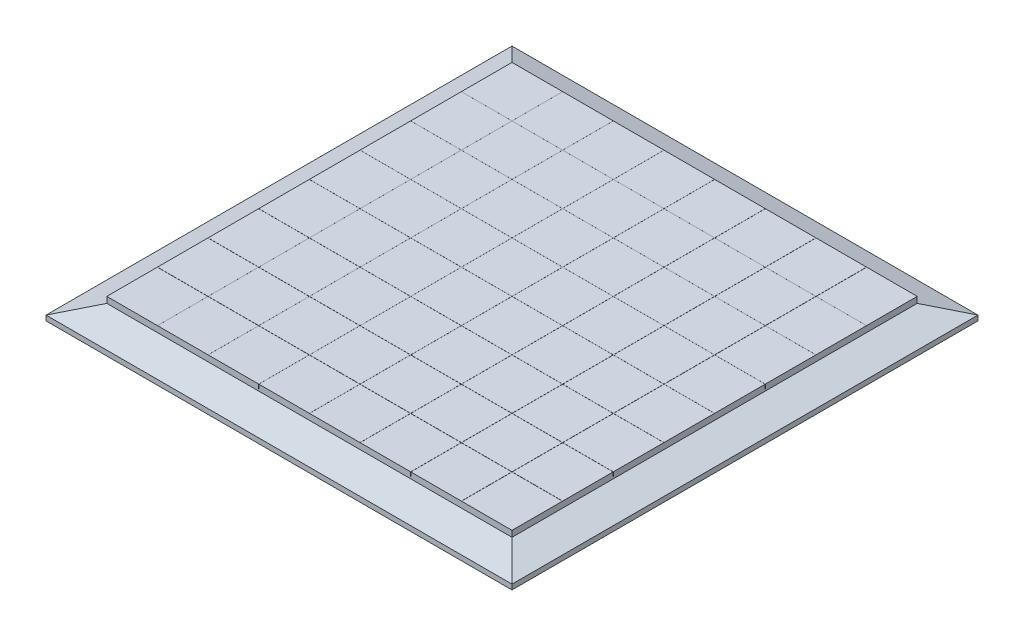
SolidWorks part; units mm, degrees
ref_plane "Ön Düzlem" through (0, 0, 0) normal (0, 0, 1) x (1, 0, 0)
ref_plane "Üst Düzlem" through (0, 0, 0) normal (0, 1, 0) x (1, 0, 0)
ref_plane "Sağ Düzlem" through (0, 0, 0) normal (1, 0, 0) x (0, 0, -1)
sketch "Çizim1" plane through (0, 0, 0) normal (0, 1, 0) x (1, 0, 0)
  line L19 (-230, 230) -> (230, 230)
  line L20 (-230, 230) -> (-230, -230)
  line L21 (-230, -230) -> (230, -230)
  line L22 (230, 230) -> (230, -230)
  line L23 (-230, 230) -> (230, -230) construction
  line L24 (-230, -230) -> (230, 230) construction
  dimension "D1" = 460
  dimension "D2" = 230
  dimension "D3" = 460
  dimension "D4" = 230
extrude "Yükseklik-Ekstrüzyon1" add sketch "Çizim1" along normal blind 15
chamfer "Pah1" distance 10 distance2 30 4 edges at (0, 15, 230) (0, 15, -230) (230, 15, 0) (-230, 15, 0)
sketch "Çizim3" plane through (0, 15, 0) normal (0, 1, 0) x (1, 0, 0)
  line L1 (-200, -200) -> (200, -200)
  line L2 (-200, -200) -> (-200, 200)
  line L3 (-200, 200) -> (200, 200)
  line L4 (200, -200) -> (200, 200)
  line L5 (-200, -200) -> (200, 200) construction
  line L6 (-200, 200) -> (200, -200) construction
  point P0 (0, 0)
extrude "Yükseklik-Ekstrüzyon2" add sketch "Çizim3" along normal blind 2
sketch "Çizim4" plane through (0, 17, 0) normal (0, 1, 0) x (1, 0, 0)
  line L0 (-150, 200) -> (-150, -200)
  line L1 (-200, 200) -> (200, 200)
  line L2 (-200, 200) -> (-200, -200)
  line L3 (-200, -200) -> (200, -200)
  line L4 (200, 200) -> (200, -200)
  line L5 (-100, 200) -> (-100, -200)
  line L6 (-50, 200) -> (-50, -200)
  line L7 (0, 200) -> (0, -200)
  line L8 (50, 200) -> (50, -200)
  line L9 (100, 200) -> (100, -200)
  line L10 (150, 200) -> (150, -200)
  line L11 (-200, 150) -> (200, 150)
  line L12 (-200, 100) -> (200, 100)
  line L13 (-200, 50) -> (200, 50)
  line L14 (-200, 0) -> (200, 0)
  line L15 (-200, -50) -> (200, -50)
  line L16 (-200, -100) -> (200, -100)
  line L17 (-200, -150) -> (200, -150)
  line L18 (-149.98, 200) -> (-149.98, -200)
  line L19 (-99.96, 200) -> (-99.96, -200)
  line L20 (-49.94, 200) -> (-49.94, -200)
  line L21 (0.08, 200) -> (0.08, -200)
  line L22 (50.1, 200) -> (50.1, -200)
  line L23 (100.12, 200) -> (100.12, -200)
  line L24 (150.14, 200) -> (150.14, -200)
  line L25 (-200, 149.98) -> (200, 149.98)
  line L26 (-200, 99.96) -> (200, 99.96)
  line L27 (-200, 49.94) -> (200, 49.94)
  line L28 (-200, -0.08) -> (200, -0.08)
  line L29 (-200, -50.1) -> (200, -50.1)
  line L30 (-200, -100.12) -> (200, -100.12)
  line L31 (-200, -150.14) -> (200, -150.14)
  point P0 (0, 0)
  point P1 (0, 0)
  line M2 (200, 200) -> (-200, 200)
  line M3 (-200, 200) -> (-200, -200)
  line M4 (-200, -200) -> (200, -200)
extrude "Yükseklik-Ekstrüzyon6" add sketch "Çizim4" along normal blind 4 contours L1 L18 L11 L5 | L25 L12 L0 M3 | L27 L14 L0 M3 | L26 L18 L13 L5 | L25 L19 L12 L6 | L1 L20 L11 L7 | L29 L16 L0 M3 | L28 L18 L15 L5 | L27 L19 L14 L6 | L26 L20 L13 L7 | L25 L21 L12 L8 | L1 L22 L11 L9 | L24 L11 L4 M2 | L25 L23 L12 L10 | L26 L22 L13 L9 | L27 L21 L14 L8 | L28 L20 L15 L7 | L29 L19 L16 L6 | L30 L18 L17 L5 | L31 L0 M3 M4 | L31 L19 L6 M4 | L30 L20 L17 L7 | L29 L21 L16 L8 | L28 L22 L15 L9 | L27 L23 L14 L10 | L26 L24 L13 L4 | L28 L24 L15 L4 | L29 L23 L16 L10 | L30 L22 L17 L9 | L31 L21 L8 M4 | L31 L23 L10 M4 | L30 L24 L17 L4
sketch "Çizim5" plane through (0, 17, 0) normal (0, 1, 0) x (1, 0, 0)
  line L0 (-150, 200) -> (-150, -200)
  line L1 (-200, 200) -> (200, 200)
  line L2 (-200, 200) -> (-200, -200)
  line L3 (-200, -200) -> (200, -200)
  line L4 (200, 200) -> (200, -200)
  line L5 (-100, 200) -> (-100, -200)
  line L6 (-50, 200) -> (-50, -200)
  line L7 (0, 200) -> (0, -200)
  line L8 (50, 200) -> (50, -200)
  line L9 (100, 200) -> (100, -200)
  line L10 (150, 200) -> (150, -200)
  line L11 (-200, 150) -> (200, 150)
  line L12 (-200, 100) -> (200, 100)
  line L13 (-200, 50) -> (200, 50)
  line L14 (-200, 0) -> (200, 0)
  line L15 (-200, -50) -> (200, -50)
  line L16 (-200, -100) -> (200, -100)
  line L17 (-200, -150) -> (200, -150)
  line L18 (-149.98, 200) -> (-149.98, -200)
  line L19 (-99.96, 200) -> (-99.96, -200)
  line L20 (-49.94, 200) -> (-49.94, -200)
  line L21 (0.08, 200) -> (0.08, -200)
  line L22 (50.1, 200) -> (50.1, -200)
  line L23 (100.12, 200) -> (100.12, -200)
  line L24 (150.14, 200) -> (150.14, -200)
  line L25 (-200, 149.98) -> (200, 149.98)
  line L26 (-200, 99.96) -> (200, 99.96)
  line L27 (-200, 49.94) -> (200, 49.94)
  line L28 (-200, -0.08) -> (200, -0.08)
  line L29 (-200, -50.1) -> (200, -50.1)
  line L30 (-200, -100.12) -> (200, -100.12)
  line L31 (-200, -150.14) -> (200, -150.14)
  point P0 (0, 0)
  point P1 (0, 0)
extrude "Yükseklik-Ekstrüzyon7" add sketch "Çizim5" along normal blind 3.999 contours L2 L11 L0 L1 | L25 L18 L12 L5 | L1 L19 L11 L6 | L1 L21 L11 L8 | L25 L20 L12 L7 | L26 L19 L13 L6 | L26 L2 L13 L0 | L27 L18 L14 L5 | L28 L19 L15 L6 | L27 L20 L14 L7 | L26 L21 L13 L8 | L25 L22 L12 L9 | L1 L23 L11 L10 | L25 L24 L12 L4 | L26 L23 L13 L10 | L27 L22 L14 L9 | L28 L21 L15 L8 | L29 L20 L16 L7 | L30 L19 L17 L6 | L29 L18 L16 L5 | L28 L2 L15 L0 | L30 L2 L17 L0 | L31 L18 L3 L5 | L31 L20 L3 L7 | L30 L21 L17 L8 | L29 L22 L16 L9 | L31 L22 L3 L9 | L30 L23 L17 L10 | L31 L24 L3 L4 | L29 L24 L16 L4 | L28 L23 L15 L10 | L27 L24 L14 L4
